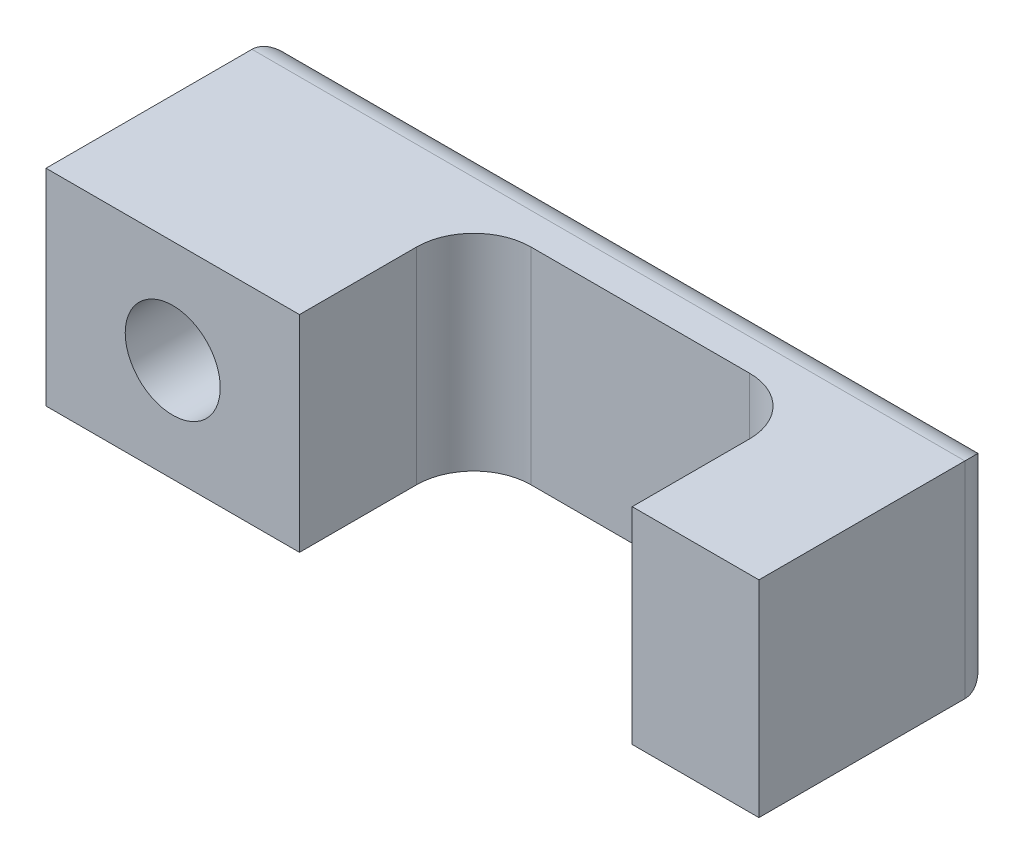
SolidWorks part; units mm, degrees
ref_plane "Front Plane" through (0, 0, 0) normal (0, 0, 1) x (1, 0, 0)
ref_plane "Top Plane" through (0, 0, 0) normal (0, 1, 0) x (1, 0, 0)
ref_plane "Right Plane" through (0, 0, 0) normal (1, 0, 0) x (0, 0, -1)
sketch "Side" plane through (0, 0, 0) normal (0, 1, 0) x (1, 0, 0)
  line L1 (0, 0) -> (22.5, 0)
  line L2 (0, 0) -> (0, 7.5)
  line L3 (0, 7.5) -> (22.5, 7.5)
  line L4 (22.5, 0) -> (22.5, 7.5)
  dimension "D1" = 22.5
  dimension "D2" = 7.5
extrude "Side_Ex" add sketch "Side" along normal blind 6.5
sketch "Wire" plane through (0, 0, 0) normal (0, 1, 0) x (1, 0, 0)
  line L0 (0, 0) -> (22.5, 0) construction
  line L1 (16.7, 5.5) -> (9.8, 5.5)
  line L2 (18.5, 3.7) -> (18.5, 0)
  line L3 (18.5, 0) -> (8, 0)
  line L4 (8, 3.7) -> (8, 0)
  line L5 (0, 7.5) -> (0, 0) construction
  line L7 (22.5, 0) -> (22.5, 7.5) construction
  line L8 (22.5, 7.5) -> (0, 7.5) construction
  arc A0 (18.5, 3.7) -> (16.7, 5.5) centre (16.7, 3.7) ccw
  arc A1 (8, 3.7) -> (9.8, 5.5) centre (9.8, 3.7) cw
  dimension "D4" = 1.8
  dimension "D5" = 1.8
  dimension "D1" = 8
  dimension "D2" = 4
  dimension "D3" = 2
ref_plane "Plane1" through (0, 0, -7.5) normal (0, 0, -1) x (-1, 0, 0)
sketch "Hole" plane through (0, 0, -7.5) normal (0, 0, -1) x (-1, 0, 0)
  line L0 (0, 6.5) -> (0, 0) construction
  line L1 (-22.5, 6.5) -> (0, 6.5) construction
  circle A0 centre (-4, 3.25) radius 1.5
  dimension "D1" = 4
  dimension "D3" = 3
  dimension "D2" = 3.25
extrude "Hole_Cut" cut sketch "Hole" against normal through all
extrude "Wire_Cut" cut sketch "Wire" along normal through all
fillet "Fillet1" radius 1 4 edges at (22.5, 3.25, -7.5) (11.25, 6.5, -7.5) (11.25, 0, -7.5) (0, 3.25, -7.5)
